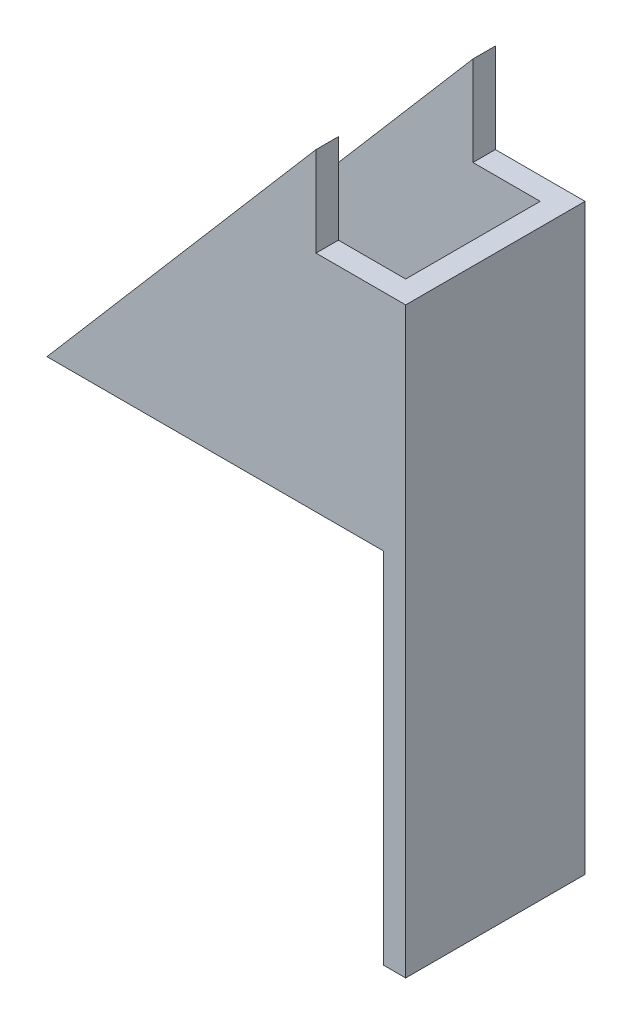
SolidWorks part; units mm, degrees
ref_plane "Front Plane" through (0, 0, 0) normal (0, 0, 1) x (1, 0, 0)
ref_plane "Top Plane" through (0, 0, 0) normal (0, 1, 0) x (1, 0, 0)
ref_plane "Right Plane" through (0, 0, 0) normal (1, 0, 0) x (0, 0, -1)
sketch "Sketch1" plane through (0, 0, 0) normal (0, 0, 1) x (1, 0, 0)
  line L0 (19.05, -50.8) -> (19.05, 0)
  line L3 (19.05, -50.8) -> (22.225, -50.8)
  line L4 (22.225, 31.75) -> (22.225, -50.8)
  line L7 (19.05, 0) -> (-28.575, 0)
  line L8 (-28.575, 0) -> (9.525, 44.45)
  line L9 (22.225, 31.75) -> (9.525, 31.75)
  line L10 (9.525, 44.45) -> (9.525, 31.75)
  point P0 (0, 0)
  dimension "D1" = 3.175
  dimension "D2" = 95.25
  dimension "D3" = 50.8
  dimension "D4" = 12.7
  dimension "D5" = 12.7
extrude "Boss-Extrude1" add sketch "Sketch1" along normal mid plane 25.4
sketch "Sketch2" plane through (0, 0, 0) normal (0, -1, 0) x (1, 0, 0)
  line L0 (-25.4, 9.525) -> (19.05, 9.525)
  line L5 (19.05, 9.525) -> (19.05, -9.525)
  line L6 (-25.4, -9.525) -> (19.05, -9.525)
  line L7 (-25.4, 9.525) -> (-25.4, -9.525)
extrude "Cut-Extrude1" cut sketch "Sketch2" against normal through all
